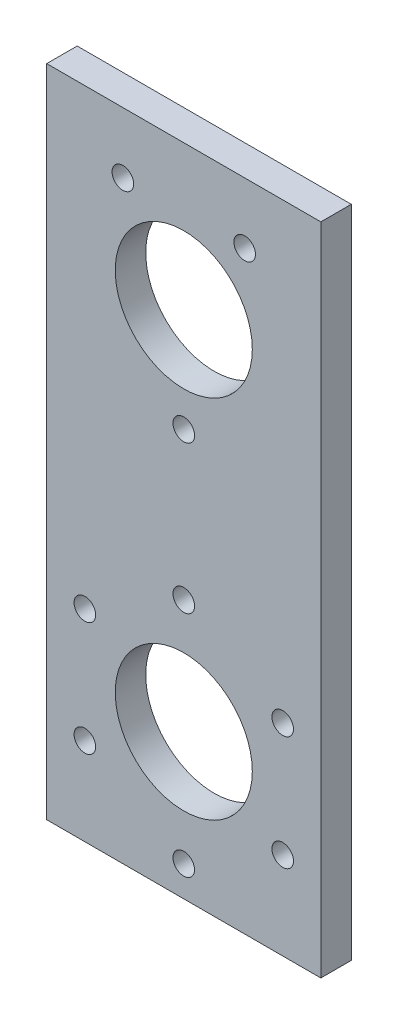
SolidWorks part; units mm, degrees
material "6061-T6 (SS)"
ref_plane "Front Plane" through (0, 0, 0) normal (0, 0, 1) x (1, 0, 0)
ref_plane "Top Plane" through (0, 0, 0) normal (0, 1, 0) x (1, 0, 0)
ref_plane "Right Plane" through (0, 0, 0) normal (1, 0, 0) x (0, 0, -1)
sketch "Sketch1" plane through (0, 0, 0) normal (0, 0, 1) x (1, 0, 0)
  line L0 (0, -38.1) -> (0, 38.1) construction
  line L2 (-28.575, 68.2625) -> (28.575, 68.2625)
  line L3 (-28.575, 68.2625) -> (-28.575, -68.2625)
  line L4 (-28.575, -68.2625) -> (28.575, -68.2625)
  line L5 (28.575, 68.2625) -> (28.575, -68.2625)
  line L6 (-28.575, 68.2625) -> (28.575, -68.2625) construction
  line L7 (-28.575, -68.2625) -> (28.575, 68.2625) construction
  circle A0 centre (0, 38.1) radius 14.2875
  circle A1 centre (0, -38.1) radius 14.2875
  point P7 (0, 0)
  point P18 (0, -38.1)
  dimension "D1" = 28.575
  dimension "D2" = 76.2
  dimension "D6" = 136.525
  dimension "D7" = 57.15
extrude "Boss-Extrude1" add sketch "Sketch1" along normal mid plane 6.35
hole_wizard "#8 Clearance Hole1" positions "Sketch3" profile "Sketch2" hole size "#8" standard "ANSI Inch" end condition through all
sketch "Sketch3" plane through (0, 0, 3.175) normal (0, 0, 1) x (1, 0, 0)
  circle A0 centre (0, -38.1) radius 14.2875 construction
  point P0 (0, -14.2875)
  point P10 (20.6222, -26.1937)
  point P11 (20.6222, -50.0062)
  point P12 (0, -61.9125)
  point P13 (-20.6222, -50.0063)
  point P14 (-20.6222, -26.1938)
  point P15 (0, -38.1)
  dimension "D1" = 23.8125
  dimension "D2" = 6
sketch "Sketch2" plane through (0, -14.2875, 3.175) normal (1, 0, 0) x (0, -1, 0)
  line L0 (0, 0) -> (0, 6.35)
  line L1 (0, 6.35) -> (2.2479, 6.35)
  line L2 (2.2479, 6.35) -> (2.2479, 0)
  line L5 (2.2479, 0) -> (0, 0)
  line L11 (0, -6.35) -> (0, 107.95) construction
  dimension "Thru Hole Dia." = 4.4958
  dimension "Thru Hole Depth" = 6.35
hole_wizard "#8 Clearance Hole2" positions "Sketch7" profile "Sketch5" hole size "#8" standard "ANSI Inch" end condition through all
sketch "Sketch7" plane through (0, 0, 3.175) normal (0, 0, 1) x (1, 0, 0)
  line L0 (-12.7, 55.5625) -> (12.7, 55.5625) construction
  line L2 (28.575, 68.2625) -> (-28.575, 68.2625) construction
  circle A3 centre (0, 38.1) radius 15.875
  circle A4 centre (0, 38.1) radius 15.875 construction
  circle A5 centre (-12.7, 55.5625) radius 7.9375 construction
  circle A8 centre (0, 16.51) radius 7.9375 construction
  point P0 (-12.7, 55.5625)
  point P2 (12.7, 55.5625)
  point P9 (0, 55.5625)
  point P29 (0, 16.51)
  dimension "D4" = 15.875
  dimension "D1" = 25.4
  dimension "D2" = 12.7
  dimension "D5" = 21.59
  dimension "D3" = 1.5875
sketch "Sketch5" plane through (-12.7, 55.5625, 3.175) normal (1, 0, 0) x (0, -1, 0)
  line L0 (0, 0) -> (0, 6.35)
  line L1 (0, 6.35) -> (2.2479, 6.35)
  line L2 (2.2479, 6.35) -> (2.2479, 0)
  line L5 (2.2479, 0) -> (0, 0)
  line L11 (0, -6.35) -> (0, 107.95) construction
  dimension "Thru Hole Dia." = 4.4958
  dimension "Thru Hole Depth" = 6.35
